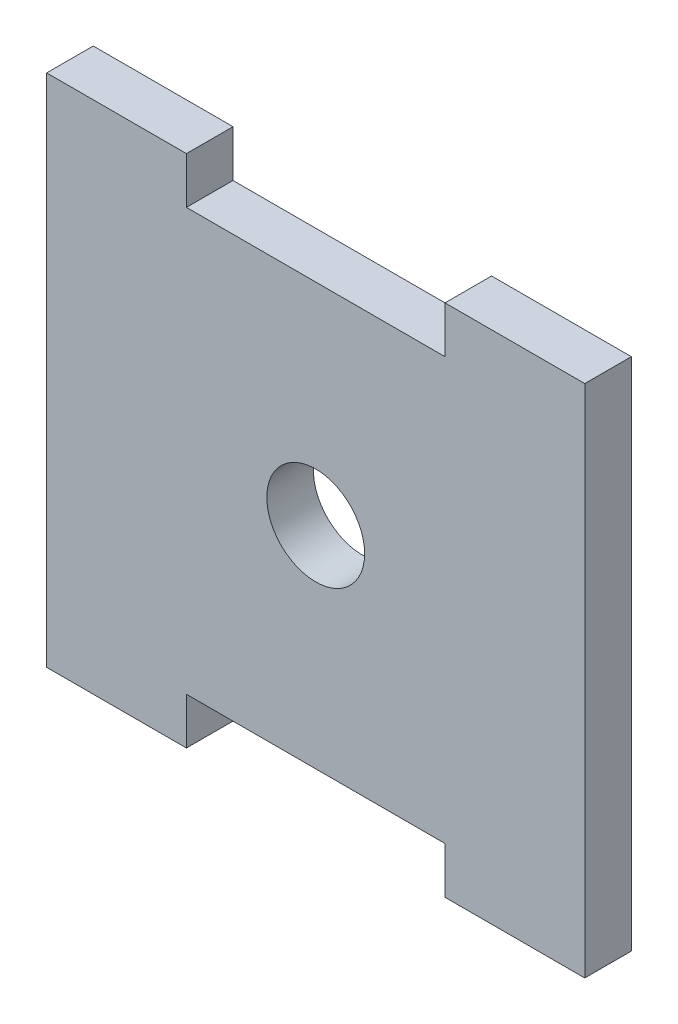
SolidWorks part; units mm, degrees
ref_plane "前视基准面" through (0, 0, 0) normal (0, 0, 1) x (1, 0, 0)
ref_plane "上视基准面" through (0, 0, 0) normal (0, 1, 0) x (1, 0, 0)
ref_plane "右视基准面" through (0, 0, 0) normal (1, 0, 0) x (0, 0, -1)
sketch "草图1" plane through (0, 0, 0) normal (0, 0, 1) x (1, 0, 0)
  line L0 (0, 0) -> (17.1, 0) construction
  line L1 (8.55, 0) -> (8.55, 1.7609) construction
  line L2 (-3, 1) -> (3, 1)
  line L3 (-3, 1) -> (-3, -1)
  line L4 (-3, -1) -> (3, -1) construction
  line L5 (3, 1) -> (3, -1)
  line L6 (-3, 1) -> (3, -1) construction
  line L7 (-3, -1) -> (3, 1) construction
  line L8 (14.1, 1) -> (14.1, -1)
  line L9 (20.1, 1) -> (20.1, -1)
  line L10 (20.1, 1) -> (14.1, 1)
  line L11 (3, -1) -> (14.1, -1)
  line L12 (-4.7034, -10.05) -> (23.2867, -10.05) construction
  line L13 (-3, -19.1) -> (3, -21.1) construction
  line L14 (-3, -21.1) -> (3, -19.1) construction
  line L15 (-3, -19.1) -> (3, -19.1) construction
  line L16 (8.55, -20.1) -> (8.55, -21.8609) construction
  line L17 (0, -20.1) -> (17.1, -20.1) construction
  line L18 (3, -19.1) -> (14.1, -19.1)
  line L19 (20.1, -21.1) -> (14.1, -21.1)
  line L20 (20.1, -21.1) -> (20.1, -19.1)
  line L21 (14.1, -21.1) -> (14.1, -19.1)
  line L22 (3, -21.1) -> (3, -19.1)
  line L23 (-3, -21.1) -> (-3, -19.1)
  line L24 (-3, -21.1) -> (3, -21.1)
  line L25 (-3, -19.1) -> (-3, -1)
  line L26 (20.1, -1) -> (20.1, -19.1)
  line L27 (8.55, -1) -> (8.55, -19.1) construction
  circle A0 centre (8.55, -10.05) radius 2.1
  dimension "D1" = 17.1
  dimension "D2" = 2
  dimension "D3" = 6
  dimension "D4" = 18.1
extrude "凸台-拉伸1" add sketch "草图1" along normal blind 2
